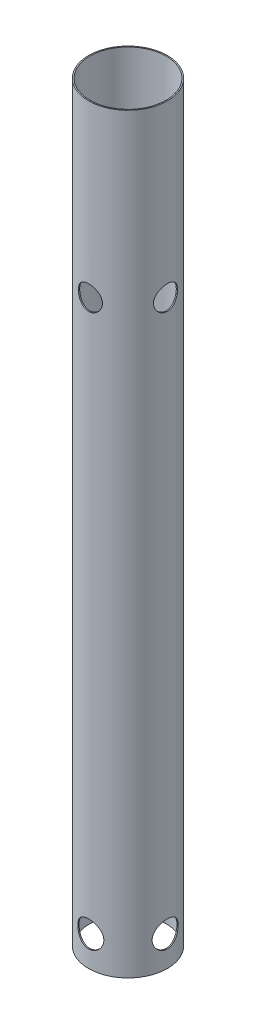
SolidWorks part; units mm, degrees
ref_plane "Front Plane" through (0, 0, 0) normal (0, 0, 1) x (1, 0, 0)
ref_plane "Top Plane" through (0, 0, 0) normal (0, 1, 0) x (1, 0, 0)
ref_plane "Right Plane" through (0, 0, 0) normal (1, 0, 0) x (0, 0, -1)
sketch "Sketch2" plane through (0, 0, 0) normal (0, 1, 0) x (1, 0, 0)
  circle A0 centre (0, 0) radius 38.15
  circle A1 centre (0, 0) radius 39.3
extrude "Boss-Extrude1" add sketch "Sketch2" along normal blind 750
sketch "Sketch3" plane through (0, 0, 0) normal (0, 0, 1) x (1, 0, 0)
  line L0 (38.15, 750) -> (-38.15, 750) construction
  circle A0 centre (0, 30) radius 13
  circle A1 centre (0, 580) radius 12
  point P2 (0, 0)
  dimension "D1" = 30
  dimension "D2" = 170
extrude "Cut-Extrude1" cut sketch "Sketch3" against normal through all
ref_axis "Axis1" through (0, 750, 0) along (0, -1, 0)
pattern_circular "CirPattern1" count 4 over 360 about axis through (0, 750, 0) along (0, -1, 0) of "Cut-Extrude1"
